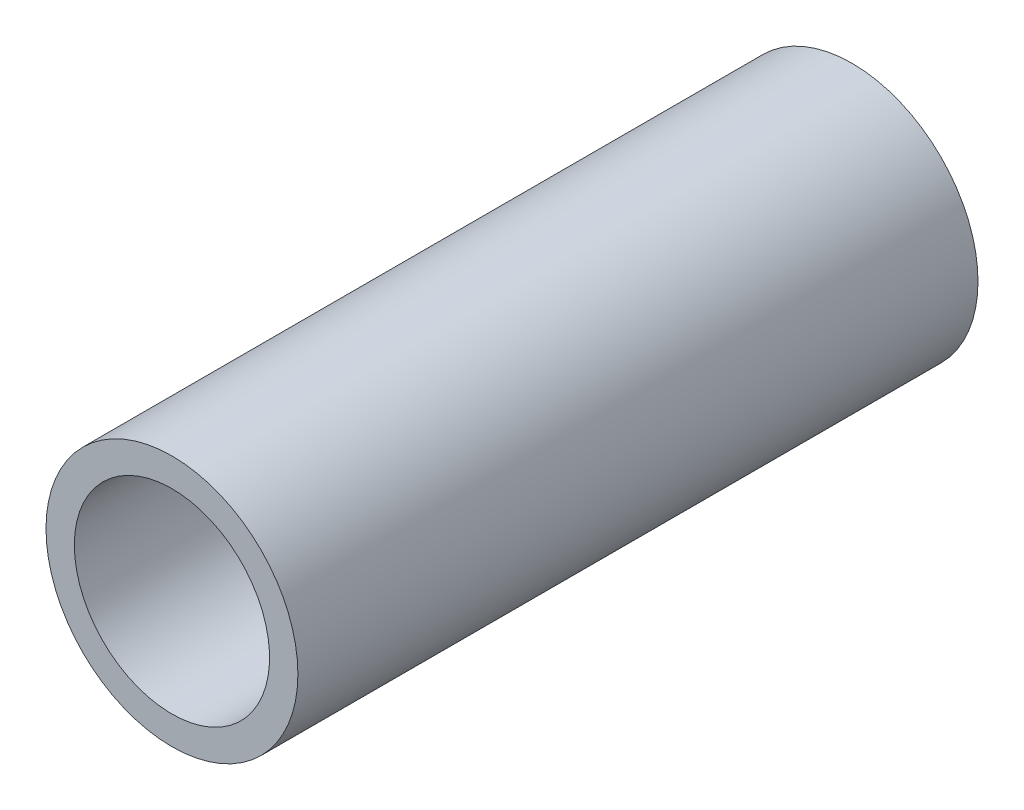
SolidWorks part; units mm, degrees
ref_plane "Спереди" through (0, 0, 0) normal (0, 0, 1) x (1, 0, 0)
ref_plane "Сверху" through (0, 0, 0) normal (0, 1, 0) x (1, 0, 0)
ref_plane "Справа" through (0, 0, 0) normal (1, 0, 0) x (0, 0, -1)
sketch "Эскиз1" plane through (0, 0, 0) normal (0, 0, 1) x (1, 0, 0)
  circle A0 centre (0, 0) radius 1
  circle A1 centre (0, 0) radius 0.775
extrude "Бобышка-Вытянуть1" add sketch "Эскиз1" along normal blind 5.4
